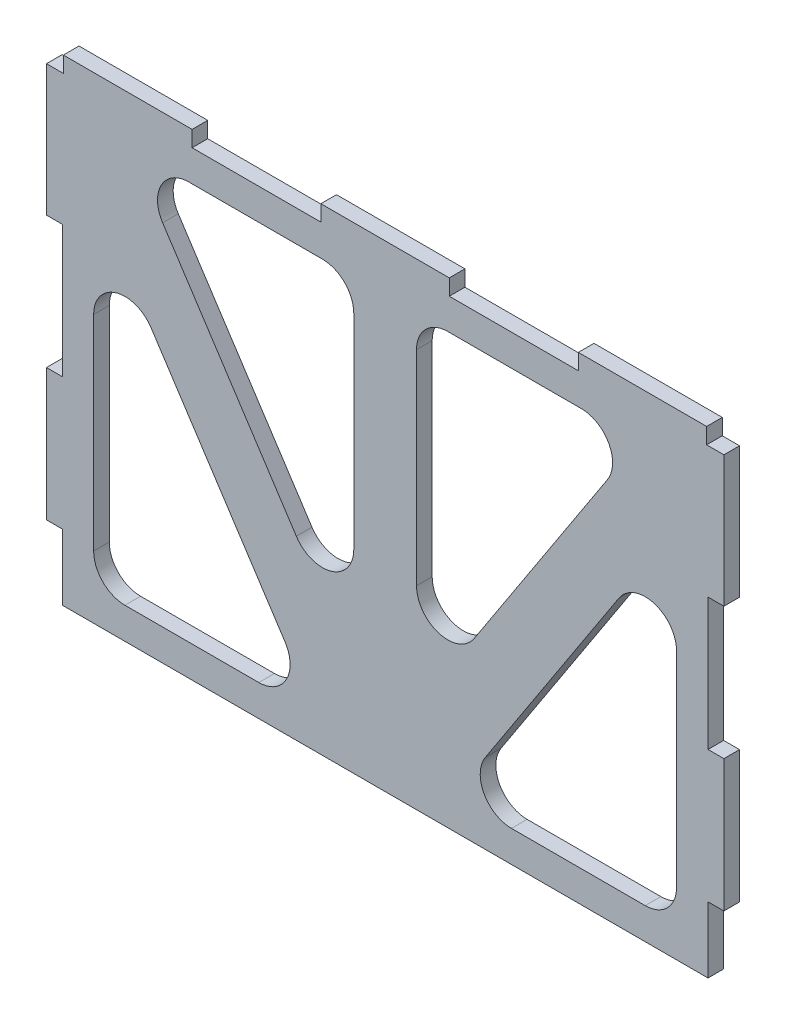
SolidWorks part; units mm, degrees
ref_plane "Front Plane" through (0, 0, 0) normal (0, 0, 1) x (1, 0, 0)
ref_plane "Top Plane" through (0, 0, 0) normal (0, 1, 0) x (1, 0, 0)
ref_plane "Right Plane" through (0, 0, 0) normal (1, 0, 0) x (0, 0, -1)
sketch "Sketch1" plane through (0, 0, 0) normal (0, 0, 1) x (1, 0, 0)
  line L0 (-237.2346, -129.6359) -> (-237.2346, -87.4578)
  line L1 (-237.2346, -87.4578) -> (-247.4011, -87.4578)
  line L2 (-247.4011, -87.4578) -> (-247.4011, -3.1016)
  line L3 (-247.4011, -3.1016) -> (-237.2346, -3.1016)
  line L4 (-237.2346, -3.1016) -> (-237.2346, 81.2546)
  line L5 (-237.2346, 81.2546) -> (-247.4011, 81.2546)
  line L6 (-247.4011, 81.2546) -> (-247.4011, 165.1107)
  line L7 (-247.4011, 165.1107) -> (-236.6058, 165.1107)
  line L8 (-237.2346, -129.6359) -> (175.503, -129.6359)
  line L9 (175.503, -129.6359) -> (175.503, -87.4578)
  line L10 (175.503, -87.4578) -> (185.6694, -87.4578)
  line L11 (185.6694, -87.4578) -> (185.6694, -3.1016)
  line L12 (185.6694, -3.1016) -> (175.503, -3.1016)
  line L13 (175.503, -3.1016) -> (175.503, 81.2546)
  line L14 (175.503, 81.2546) -> (185.6694, 81.2546)
  line L15 (185.6694, 81.2546) -> (185.6694, 165.1107)
  line L16 (185.6694, 165.1107) -> (174.6267, 165.1107)
  line L17 (174.6267, 165.1107) -> (174.6267, 175.2916)
  line L18 (174.6267, 175.2916) -> (92.6098, 175.2916)
  line L19 (92.6098, 175.2916) -> (92.6098, 165.1107)
  line L20 (92.6098, 165.1107) -> (10.1107, 165.1107)
  line L21 (10.1107, 165.1107) -> (10.1107, 175.2916)
  line L22 (10.1107, 175.2916) -> (-71.987, 175.2916)
  line L23 (-71.987, 175.2916) -> (-71.987, 165.1107)
  line L24 (-71.987, 165.1107) -> (-154.2948, 165.1107)
  line L25 (-154.2948, 165.1107) -> (-154.2948, 175.2916)
  line L26 (-154.2948, 175.2916) -> (-236.6058, 175.2916)
  line L27 (-236.6058, 175.2916) -> (-236.6058, 165.1107)
  line L28 (-50.9382, 125.1107) -> (-50.9382, -5.689)
  line L29 (-156.4007, 145.1107) -> (-70.9382, 145.1107)
  line L30 (-217.2346, 41.3487) -> (-217.2346, -89.6359)
  line L31 (-197.2346, -109.6359) -> (-111.6512, -109.6359)
  line L33 (-10.8204, 125.1107) -> (-10.8204, -5.6211)
  line L34 (-173.1437, 114.1711) -> (-87.6811, -16.6285)
  line L35 (-180.4917, 52.2882) -> (-94.9083, -78.6963)
  line L36 (-217.2453, 145.1037) -> (-50.8429, -109.5736) construction
  line L37 (-30.9382, 175.2916) -> (-30.8658, -129.6359) construction
  line L38 (118.6418, 52.3104) -> (33.1375, -78.6888)
  line L39 (155.3833, 145.1921) -> (-10.8983, -109.5641) construction
  line L40 (111.2575, 114.1791) -> (25.9277, -16.5528)
  line L41 (49.8827, -109.6205) -> (135.387, -109.6329)
  line L42 (155.3301, 145.1107) -> (155.503, 145.1107)
  line L43 (9.1796, 145.1107) -> (94.5094, 145.1107)
  line L44 (155.3899, 41.3787) -> (155.3899, -89.6329)
  arc A0 (-180.4917, 52.2882) -> (-217.2346, 41.3487) centre (-197.2346, 41.3487) ccw
  arc A1 (-197.2346, -109.6359) -> (-217.2346, -89.6359) centre (-197.2346, -89.6359) cw
  arc A2 (-111.6512, -109.6359) -> (-94.9083, -78.6963) centre (-111.6512, -89.6359) ccw
  arc A3 (49.8827, -109.6205) -> (33.1375, -78.6888) centre (49.8857, -89.6205) cw
  arc A4 (135.387, -109.6329) -> (155.3899, -89.6329) centre (135.3899, -89.6329) ccw
  arc A5 (155.3899, 41.3787) -> (118.6418, 52.3104) centre (135.3899, 41.3787) ccw
  arc A6 (111.2575, 114.1791) -> (94.5094, 145.1107) centre (94.5094, 125.1107) ccw
  arc A7 (9.1796, 145.1107) -> (-10.8204, 125.1107) centre (9.1796, 125.1107) ccw
  arc A8 (25.9277, -16.5528) -> (-10.8204, -5.6211) centre (9.1796, -5.6211) cw
  arc A9 (-50.9382, -5.689) -> (-87.6811, -16.6285) centre (-70.9382, -5.689) cw
  arc A10 (-50.9382, 125.1107) -> (-70.9382, 145.1107) centre (-70.9382, 125.1107) ccw
  arc A11 (-156.4007, 145.1107) -> (-173.1437, 114.1711) centre (-156.4007, 125.1107) ccw
  point P36 (131.4971, 145.1921)
  point P37 (-30.9382, 175.2916)
  point P53 (-217.2346, 108.5229)
  point P58 (-74.6929, -109.6359)
  point P61 (12.9517, -109.6151)
  point P66 (155.3899, 108.6113)
  point P71 (-10.8204, 145.1107)
  point P74 (-10.8204, -72.8537)
  point P77 (-50.9382, -72.8632)
  dimension "D4" = 20
  dimension "D1" = 304.9274
  dimension "D2" = 20
  dimension "D3" = 20
  dimension "D5" = 20
  dimension "D7" = 20
  dimension "D8" = 40
  dimension "D9" = 20
extrude "Boss-Extrude1" add sketch "Sketch1" along normal blind 10
